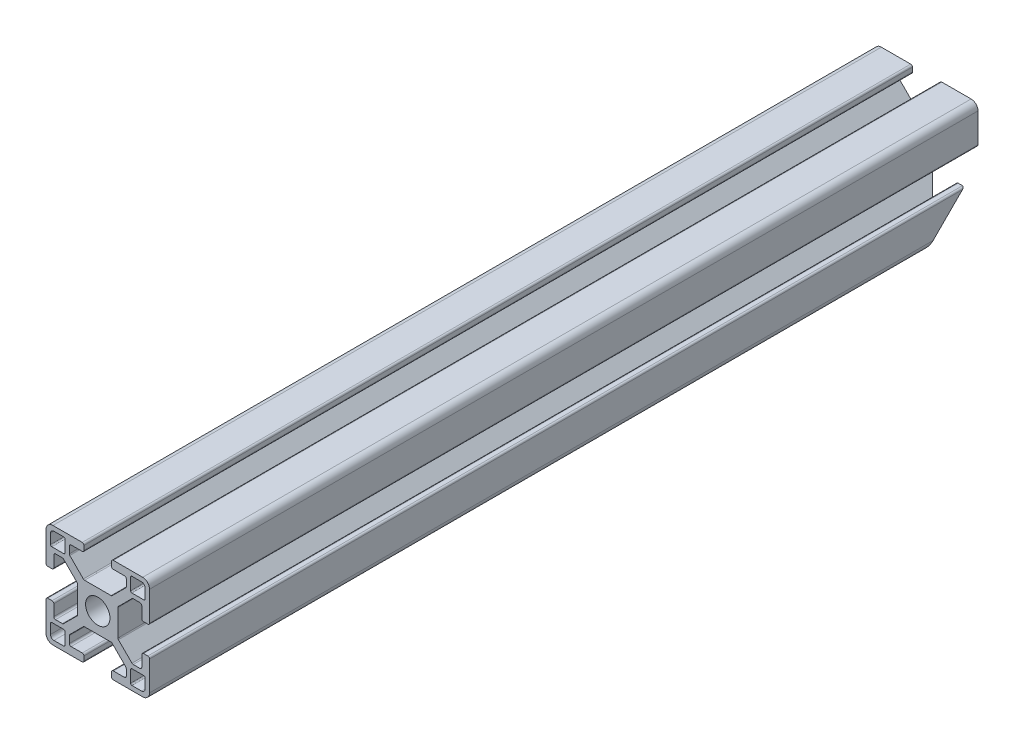
SolidWorks part; units mm, degrees
material "6063-T6"
ref_plane "Front Plane" through (0, 0, 0) normal (0, 0, 1) x (1, 0, 0)
ref_plane "Top Plane" through (0, 0, 0) normal (0, 1, 0) x (1, 0, 0)
ref_plane "Right Plane" through (0, 0, 0) normal (1, 0, 0) x (0, 0, -1)
sketch "Sketch1" plane through (0, 0, 0) normal (0, 0, 1) x (1, 0, 0)
  line L0 (3.9799, -2.4733) -> (3.1981, -1.4942) construction
  line L1 (1.4942, -3.1981) -> (2.4733, -3.9799) construction
  line L2 (-2.4733, -3.9799) -> (-1.4942, -3.1981) construction
  line L3 (-3.1981, -1.4942) -> (-3.9799, -2.4733) construction
  line L4 (-3.9799, 2.4733) -> (-3.1981, 1.4942) construction
  line L5 (-1.4942, 3.1981) -> (-2.4733, 3.9799) construction
  line L6 (2.4733, 3.9799) -> (1.4942, 3.1981) construction
  line L7 (3.1981, 1.4942) -> (3.9799, 2.4733) construction
  line L8 (-12.6999, -13.6999) -> (-9.881, -13.6999)
  line L9 (-13.6999, -9.881) -> (-13.6999, -12.6999)
  line L10 (-9.88, -9.5) -> (-13.3189, -9.5)
  line L11 (-9.5, -13.3189) -> (-9.5, -9.88)
  line L12 (13.6999, -12.6999) -> (13.6999, -9.881)
  line L13 (9.881, -13.6999) -> (12.6999, -13.6999)
  line L14 (9.5, -9.88) -> (9.5, -13.3189)
  line L15 (13.3189, -9.5) -> (9.88, -9.5)
  line L16 (9.88, 9.5) -> (13.3189, 9.5)
  line L17 (9.5, 13.3189) -> (9.5, 9.88)
  line L18 (12.6999, 13.6999) -> (9.881, 13.6999)
  line L19 (13.6999, 9.881) -> (13.6999, 12.6999)
  line L20 (-13.6999, 12.6999) -> (-13.6999, 9.881)
  line L21 (-9.881, 13.6999) -> (-12.6999, 13.6999)
  line L22 (-9.5, 9.88) -> (-9.5, 13.3189)
  line L23 (-13.3189, 9.5) -> (-9.88, 9.5)
  line L24 (14.4999, -4) -> (13.2425, -4)
  line L25 (12.7425, -4.5) -> (12.7425, -7.7325)
  line L26 (12.2428, -8.25) -> (10.2602, -8.25)
  line L27 (9.9066, -8.1035) -> (5.9811, -4.178)
  line L28 (5.8347, -3.8245) -> (5.8347, -1.0125)
  line L29 (5.8347, -1.0125) -> (5.3247, -0.0625) construction
  line L30 (5.3247, -0.0625) -> (5.8347, 0.8875) construction
  line L31 (5.8347, 0.8875) -> (5.8347, 3.8245)
  line L32 (5.9811, 4.178) -> (9.9066, 8.1035)
  line L33 (10.2602, 8.25) -> (12.2428, 8.25)
  line L34 (12.7425, 7.7325) -> (12.7425, 4.5)
  line L35 (13.2425, 4) -> (14.4999, 4)
  line L36 (14.9999, 4.5) -> (14.9999, 12.9999)
  line L37 (12.9999, 14.9999) -> (4.5, 14.9999)
  line L38 (4, 14.4999) -> (4, 13.2425)
  line L39 (4.5, 12.7425) -> (7.7325, 12.7425)
  line L40 (8.25, 12.2428) -> (8.25, 10.2602)
  line L41 (8.1035, 9.9066) -> (4.178, 5.9811)
  line L42 (3.8245, 5.8347) -> (0.95, 5.8347)
  line L43 (0.95, 5.8347) -> (0, 5.3247) construction
  line L44 (0, 5.3247) -> (-0.95, 5.8347) construction
  line L45 (-0.95, 5.8347) -> (-3.8245, 5.8347)
  line L46 (-4.178, 5.9811) -> (-8.1035, 9.9066)
  line L47 (-8.25, 10.2602) -> (-8.25, 12.2428)
  line L48 (-7.7325, 12.7425) -> (-4.5, 12.7425)
  line L49 (-4, 13.2425) -> (-4, 14.4999)
  line L50 (-4.5, 14.9999) -> (-12.9999, 14.9999)
  line L51 (-14.9999, 12.9999) -> (-14.9999, 4.5)
  line L52 (-14.4999, 4) -> (-13.2425, 4)
  line L53 (-12.7425, 4.5) -> (-12.7425, 7.7325)
  line L54 (-12.2428, 8.25) -> (-10.2602, 8.25)
  line L55 (-9.9066, 8.1035) -> (-5.9811, 4.178)
  line L56 (-5.8347, 3.8245) -> (-5.8347, 0.8875)
  line L57 (-5.8347, 0.8875) -> (-5.3247, -0.0625) construction
  line L58 (-5.3247, -0.0625) -> (-5.8347, -1.0125) construction
  line L59 (-5.8347, -1.0125) -> (-5.8347, -3.8245)
  line L60 (-5.9811, -4.178) -> (-9.9066, -8.1035)
  line L61 (-10.2602, -8.25) -> (-12.2428, -8.25)
  line L62 (-12.7425, -7.7325) -> (-12.7425, -4.5)
  line L63 (-13.2425, -4) -> (-14.4999, -4)
  line L64 (-14.9999, -4.5) -> (-14.9999, -12.9999)
  line L65 (-12.9999, -14.9999) -> (-4.5, -14.9999)
  line L66 (-4, -14.4999) -> (-4, -13.2425)
  line L67 (-4.5, -12.7425) -> (-7.7325, -12.7425)
  line L68 (-8.25, -12.2428) -> (-8.25, -10.2602)
  line L69 (-8.1035, -9.9066) -> (-4.178, -5.9811)
  line L70 (-3.8245, -5.8347) -> (-0.95, -5.8347)
  line L71 (-0.95, -5.8347) -> (0, -5.3247) construction
  line L72 (0, -5.3247) -> (0.95, -5.8347) construction
  line L73 (0.95, -5.8347) -> (3.8245, -5.8347)
  line L74 (4.178, -5.9811) -> (8.1035, -9.9066)
  line L75 (8.25, -10.2602) -> (8.25, -12.2428)
  line L76 (7.7325, -12.7425) -> (4.5, -12.7425)
  line L77 (4, -13.2425) -> (4, -14.4999)
  line L78 (4.5, -14.9999) -> (12.9999, -14.9999)
  line L79 (14.9999, -12.9999) -> (14.9999, -4.5)
  line L80 (-5.8347, -1.0125) -> (-5.8347, 0.8875)
  line L81 (-0.95, 5.8347) -> (0.95, 5.8347)
  line L82 (5.8347, 0.8875) -> (5.8347, -1.0125)
  line L83 (-0.95, -5.8347) -> (0.95, -5.8347)
  arc A0 (2.4733, -3.9799) -> (3.9799, -2.4733) centre (3.1422, -3.1422) ccw construction
  arc A1 (-1.4942, -3.1981) -> (1.4942, -3.1981) centre (0, 0) ccw construction
  arc A2 (-3.9799, -2.4733) -> (-2.4733, -3.9799) centre (-3.1422, -3.1422) ccw construction
  arc A3 (-3.1981, 1.4942) -> (-3.1981, -1.4942) centre (0, 0) ccw construction
  arc A4 (-2.4733, 3.9799) -> (-3.9799, 2.4733) centre (-3.1422, 3.1422) ccw construction
  arc A5 (1.4942, 3.1981) -> (-1.4942, 3.1981) centre (0, 0) ccw construction
  arc A6 (3.9799, 2.4733) -> (2.4733, 3.9799) centre (3.1422, 3.1422) ccw construction
  arc A7 (3.1981, -1.4942) -> (3.1981, 1.4942) centre (0, 0) ccw construction
  arc A8 (-13.6999, -12.6999) -> (-12.6999, -13.6999) centre (-12.6999, -12.6999) ccw
  arc A9 (-13.3189, -9.5) -> (-13.6999, -9.881) centre (-13.3189, -9.881) ccw
  arc A10 (-9.5, -9.88) -> (-9.88, -9.5) centre (-9.88, -9.88) ccw
  arc A11 (-9.881, -13.6999) -> (-9.5, -13.3189) centre (-9.881, -13.3189) ccw
  arc A12 (12.6999, -13.6999) -> (13.6999, -12.6999) centre (12.6999, -12.6999) ccw
  arc A13 (9.5, -13.3189) -> (9.881, -13.6999) centre (9.881, -13.3189) ccw
  arc A14 (9.88, -9.5) -> (9.5, -9.88) centre (9.88, -9.88) ccw
  arc A15 (13.6999, -9.881) -> (13.3189, -9.5) centre (13.3189, -9.881) ccw
  arc A16 (9.5, 9.88) -> (9.88, 9.5) centre (9.88, 9.88) ccw
  arc A17 (9.881, 13.6999) -> (9.5, 13.3189) centre (9.881, 13.3189) ccw
  arc A18 (13.6999, 12.6999) -> (12.6999, 13.6999) centre (12.6999, 12.6999) ccw
  arc A19 (13.3189, 9.5) -> (13.6999, 9.881) centre (13.3189, 9.881) ccw
  arc A20 (14.9999, -4.5) -> (14.4999, -4) centre (14.4999, -4.5) ccw
  arc A21 (13.2425, -4) -> (12.7425, -4.5) centre (13.2425, -4.5) ccw
  arc A22 (12.2428, -8.25) -> (12.7425, -7.7325) centre (12.2428, -7.75) ccw
  arc A23 (9.9066, -8.1035) -> (10.2602, -8.25) centre (10.2602, -7.75) ccw
  arc A24 (5.8347, -3.8245) -> (5.9811, -4.178) centre (6.3347, -3.8245) ccw
  arc A25 (5.9811, 4.178) -> (5.8347, 3.8245) centre (6.3347, 3.8245) ccw
  arc A26 (10.2602, 8.25) -> (9.9066, 8.1035) centre (10.2602, 7.75) ccw
  arc A27 (12.7425, 7.7325) -> (12.2428, 8.25) centre (12.2428, 7.75) ccw
  arc A28 (12.7425, 4.5) -> (13.2425, 4) centre (13.2425, 4.5) ccw
  arc A29 (14.4999, 4) -> (14.9999, 4.5) centre (14.4999, 4.5) ccw
  arc A30 (14.9999, 12.9999) -> (12.9999, 14.9999) centre (12.9999, 12.9999) ccw
  arc A31 (4.5, 14.9999) -> (4, 14.4999) centre (4.5, 14.4999) ccw
  arc A32 (4, 13.2425) -> (4.5, 12.7425) centre (4.5, 13.2425) ccw
  arc A33 (8.25, 12.2428) -> (7.7325, 12.7425) centre (7.75, 12.2428) ccw
  arc A34 (8.1035, 9.9066) -> (8.25, 10.2602) centre (7.75, 10.2602) ccw
  arc A35 (3.8245, 5.8347) -> (4.178, 5.9811) centre (3.8245, 6.3347) ccw
  arc A36 (-4.178, 5.9811) -> (-3.8245, 5.8347) centre (-3.8245, 6.3347) ccw
  arc A37 (-8.25, 10.2602) -> (-8.1035, 9.9066) centre (-7.75, 10.2602) ccw
  arc A38 (-7.7325, 12.7425) -> (-8.25, 12.2428) centre (-7.75, 12.2428) ccw
  arc A39 (-4.5, 12.7425) -> (-4, 13.2425) centre (-4.5, 13.2425) ccw
  arc A40 (-4, 14.4999) -> (-4.5, 14.9999) centre (-4.5, 14.4999) ccw
  arc A41 (-12.9999, 14.9999) -> (-14.9999, 12.9999) centre (-12.9999, 12.9999) ccw
  arc A42 (-14.9999, 4.5) -> (-14.4999, 4) centre (-14.4999, 4.5) ccw
  arc A43 (-13.2425, 4) -> (-12.7425, 4.5) centre (-13.2425, 4.5) ccw
  arc A44 (-12.2428, 8.25) -> (-12.7425, 7.7325) centre (-12.2428, 7.75) ccw
  arc A45 (-9.9066, 8.1035) -> (-10.2602, 8.25) centre (-10.2602, 7.75) ccw
  arc A46 (-5.8347, 3.8245) -> (-5.9811, 4.178) centre (-6.3347, 3.8245) ccw
  arc A47 (-5.9811, -4.178) -> (-5.8347, -3.8245) centre (-6.3347, -3.8245) ccw
  arc A48 (-10.2602, -8.25) -> (-9.9066, -8.1035) centre (-10.2602, -7.75) ccw
  arc A49 (-12.7425, -7.7325) -> (-12.2428, -8.25) centre (-12.2428, -7.75) ccw
  arc A50 (-12.7425, -4.5) -> (-13.2425, -4) centre (-13.2425, -4.5) ccw
  arc A51 (-14.4999, -4) -> (-14.9999, -4.5) centre (-14.4999, -4.5) ccw
  arc A52 (-14.9999, -12.9999) -> (-12.9999, -14.9999) centre (-12.9999, -12.9999) ccw
  arc A53 (-4.5, -14.9999) -> (-4, -14.4999) centre (-4.5, -14.4999) ccw
  arc A54 (-4, -13.2425) -> (-4.5, -12.7425) centre (-4.5, -13.2425) ccw
  arc A55 (-8.25, -12.2428) -> (-7.7325, -12.7425) centre (-7.75, -12.2428) ccw
  arc A56 (-8.1035, -9.9066) -> (-8.25, -10.2602) centre (-7.75, -10.2602) ccw
  arc A57 (-3.8245, -5.8347) -> (-4.178, -5.9811) centre (-3.8245, -6.3347) ccw
  arc A58 (4.178, -5.9811) -> (3.8245, -5.8347) centre (3.8245, -6.3347) ccw
  arc A59 (8.25, -10.2602) -> (8.1035, -9.9066) centre (7.75, -10.2602) ccw
  arc A60 (7.7325, -12.7425) -> (8.25, -12.2428) centre (7.75, -12.2428) ccw
  arc A61 (4.5, -12.7425) -> (4, -13.2425) centre (4.5, -13.2425) ccw
  arc A62 (4, -14.4999) -> (4.5, -14.9999) centre (4.5, -14.4999) ccw
  arc A63 (12.9999, -14.9999) -> (14.9999, -12.9999) centre (12.9999, -12.9999) ccw
  arc A64 (-12.6999, 13.6999) -> (-13.6999, 12.6999) centre (-12.6999, 12.6999) ccw
  arc A65 (-9.5, 13.3189) -> (-9.881, 13.6999) centre (-9.881, 13.3189) ccw
  arc A66 (-9.88, 9.5) -> (-9.5, 9.88) centre (-9.88, 9.88) ccw
  arc A67 (-13.6999, 9.881) -> (-13.3189, 9.5) centre (-13.3189, 9.881) ccw
  circle A68 centre (0, 0) radius 3.53
extrude "Boss-Extrude1" add sketch "Sketch1" along normal mid plane 240
sketch "Sketch2" plane through (-5.8347, 0, 0) normal (-1, 0, 0) x (0, 0, 1)
  line L0 (120, 3.8245) -> (120, -3.8245) construction
  circle A0 centre (105, 0) radius 1.5
  dimension "D1" = 3
  dimension "D2" = 15
extrude "Cut-Extrude1" cut sketch "Sketch2" against normal blind 13
sketch "Sketch3" plane through (14.9999, 0, 0) normal (1, 0, 0) x (0, 0, -1)
  line L0 (120, 0) -> (105.0001, -14.9999)
  line L1 (120, -3.8245) -> (120, 3.8245) construction
  line L2 (-120, -14.9999) -> (120, -14.9999) construction
  line L3 (105.0001, -14.9999) -> (120, -14.9999)
  line L4 (120, -14.9999) -> (120, 0)
  dimension "D1" = 45
extrude "Cut-Extrude2" cut sketch "Sketch3" against normal blind 30
